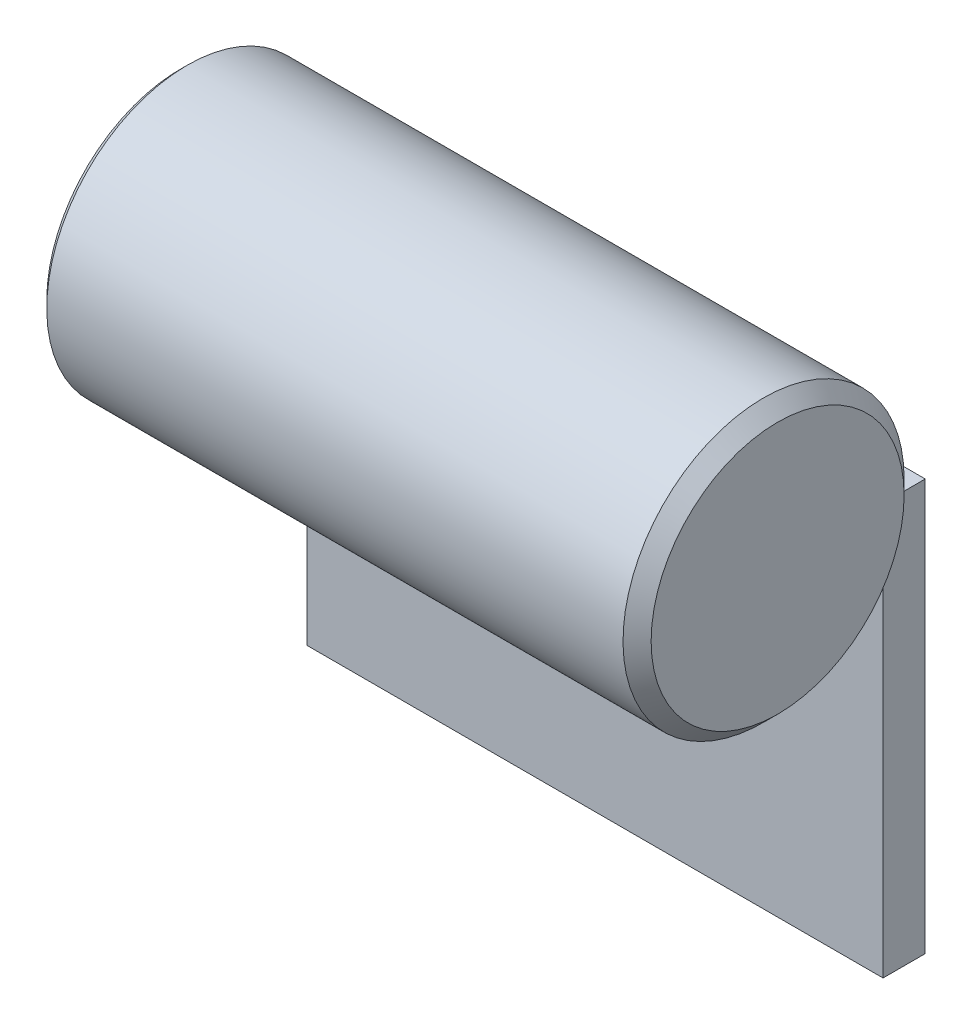
SolidWorks part; units mm, degrees
ref_plane "Спереди" through (0, 0, 0) normal (0, 0, 1) x (1, 0, 0)
ref_plane "Сверху" through (0, 0, 0) normal (0, 1, 0) x (1, 0, 0)
ref_plane "Справа" through (0, 0, 0) normal (1, 0, 0) x (0, 0, -1)
sketch "Эскиз1" plane through (0, 0, 0) normal (0, 1, 0) x (1, 0, 0)
  line L0 (92.6529, 0) -> (92.6529, 18)
  line L1 (90.6529, 20) -> (8.6529, 20)
  line L2 (7.6529, 19) -> (7.6529, 14.75)
  line L3 (7.6529, 14.75) -> (8.6529, 13.75)
  line L4 (76.7985, 0) -> (92.6529, 0)
  line L5 (102.994, 0) -> (-18.114, 0) construction
  line L6 (8.6529, 13.75) -> (71.6294, 13.75)
  line L7 (8.6529, 20) -> (7.6529, 19)
  line L8 (92.6529, 18) -> (90.6529, 20)
  line L9 (71.6294, 3.4302) -> (71.6294, 13.75)
  line L10 (71.6294, 3.4302) -> (76.7985, 0)
  point P1 (92.6529, 20)
  point P9 (7.6529, 20)
  point P10 (7.6529, 13.75)
  dimension "D1" = 1
  dimension "D2" = 45
  dimension "D3" = 1
  dimension "D4" = 45
  dimension "D5" = 2
  dimension "D6" = 45
  dimension "D7" = 6.25
revolve "Повернуть4" add sketch "Эскиз1" angle 360 about L5
sketch "Эскиз2" plane through (0, 0, 0) normal (0, 1, 0) x (1, 0, 0)
  line L0 (90.6529, 20) -> (90.6529, -20) construction
  line L6 (90.6529, 17.0037) -> (8.6529, 17.0037)
  line L7 (90.6529, 17.0037) -> (90.6529, 23.0049)
  line L8 (90.6529, 23.0049) -> (8.6529, 23.0049)
  line L9 (8.6529, 17.0037) -> (8.6529, 23.0049)
extrude "Бобышка-Вытянуть1" add sketch "Эскиз2" against normal blind 60
sketch "Эскиз3" plane through (0, 0, 0) normal (0, 1, 0) x (1, 0, 0)
  line L1 (8.6529, 23.0049) -> (90.6529, 23.0049)
  line L2 (8.6529, 23.0049) -> (8.6529, 20)
  line L3 (8.6529, 20) -> (90.6529, 20)
  line L4 (90.6529, 23.0049) -> (90.6529, 20)
extrude "Вырез-Вытянуть1" cut sketch "Эскиз3" against normal blind 1.5
